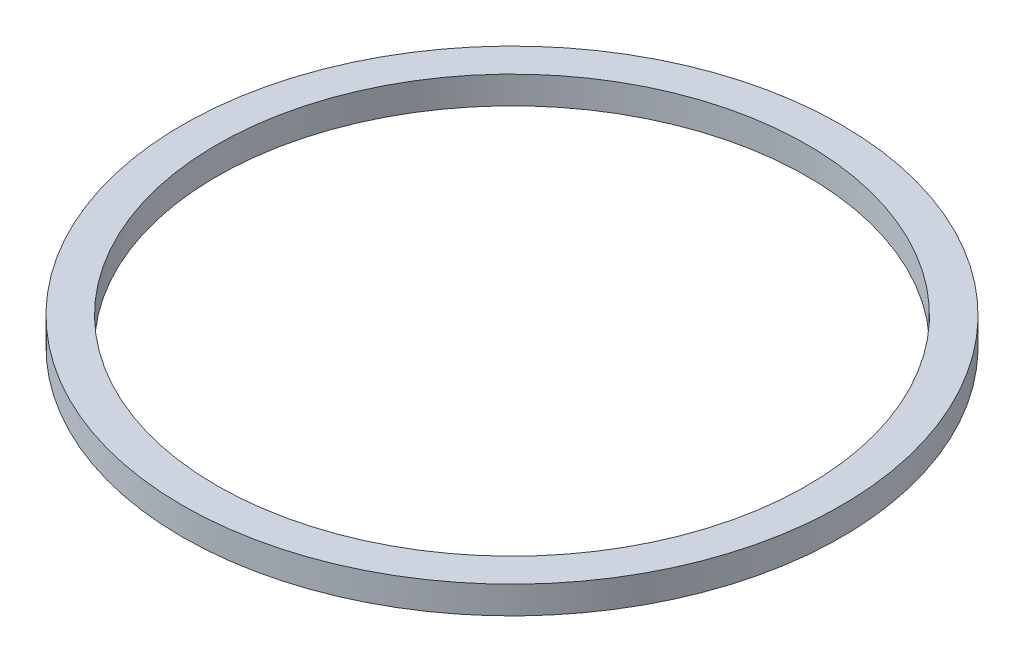
SolidWorks part; units mm, degrees
ref_plane "Front Plane" through (0, 0, 0) normal (0, 0, 1) x (1, 0, 0)
ref_plane "Top Plane" through (0, 0, 0) normal (0, 1, 0) x (1, 0, 0)
ref_plane "Right Plane" through (0, 0, 0) normal (1, 0, 0) x (0, 0, -1)
sketch "Sketch1" plane through (0, 0, 0) normal (0, 1, 0) x (1, 0, 0)
  circle A0 centre (0, 0) radius 12
  circle A1 centre (0, 0) radius 10.75
  dimension "D1" = 21.5
  dimension "D2" = 24
extrude "Boss-Extrude1" add sketch "Sketch1" along normal mid plane 1
